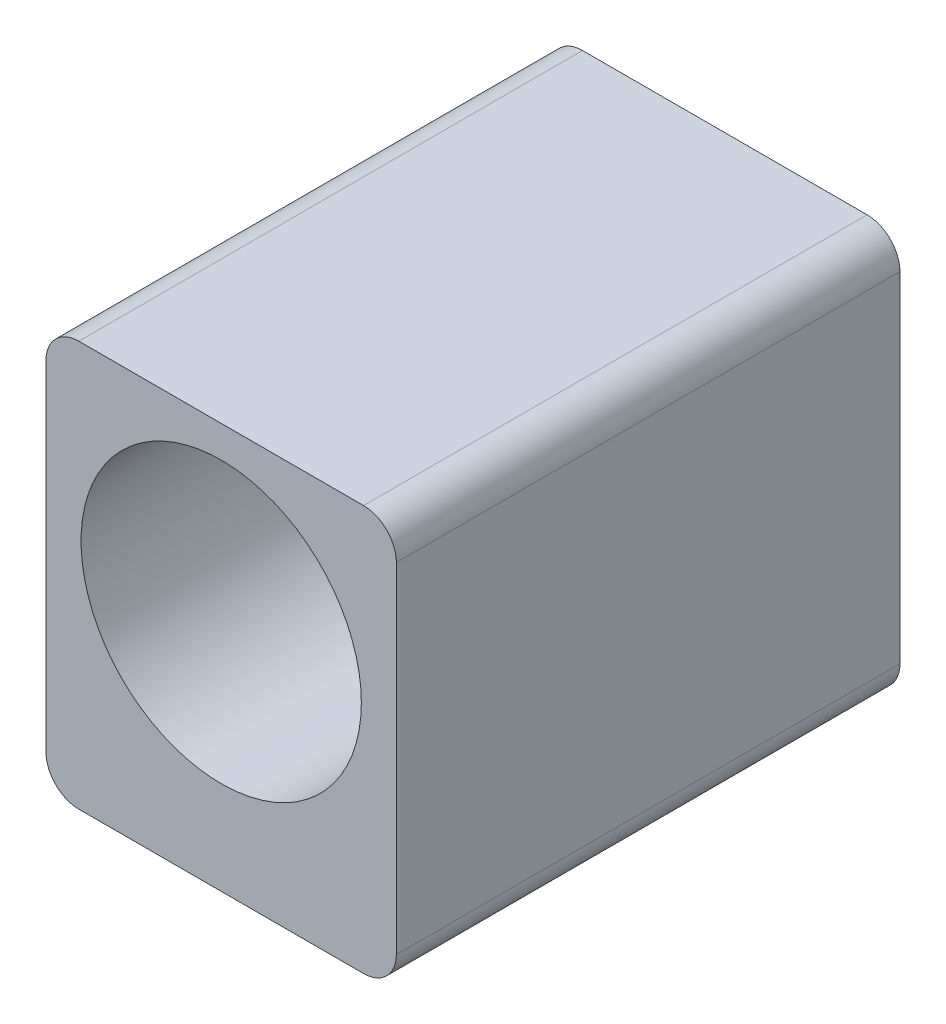
SolidWorks part; units mm, degrees
ref_plane "Front Plane" through (0, 0, 0) normal (0, 0, 1) x (1, 0, 0)
ref_plane "Top Plane" through (0, 0, 0) normal (0, 1, 0) x (1, 0, 0)
ref_plane "Right Plane" through (0, 0, 0) normal (1, 0, 0) x (0, 0, -1)
sketch "Sketch1" plane through (0, 0, 0) normal (0, 0, 1) x (1, 0, 0)
  line L0 (-13, -21.319) -> (13, -21.319)
  line L1 (16, -18.319) -> (16, 12.7)
  line L2 (13, 15.7) -> (-13, 15.7)
  line L3 (-16, 12.7) -> (-16, -18.319)
  arc A0 (13, -21.319) -> (16, -18.319) centre (13, -18.319) ccw
  arc A1 (16, 12.7) -> (13, 15.7) centre (13, 12.7) ccw
  arc A2 (-13, 15.7) -> (-16, 12.7) centre (-13, 12.7) ccw
  arc A3 (-16, -18.319) -> (-13, -21.319) centre (-13, -18.319) ccw
  circle A4 centre (0, 0) radius 12.8
extrude "Boss-Extrude1" add sketch "Sketch1" along normal mid plane 46
ref_plane "Plane1" through (0, -21.319, 0) normal (0, 1, 0) x (1, 0, 0)
sketch "Sketch2" plane through (0, -21.319, 0) normal (0, 1, 0) x (1, 0, 0)
  circle A0 centre (12, -17.5) radius 2
  circle A1 centre (-12, 17.5) radius 2
extrude "Cut-Extrude1" cut sketch "Sketch2" along normal blind 7.5
